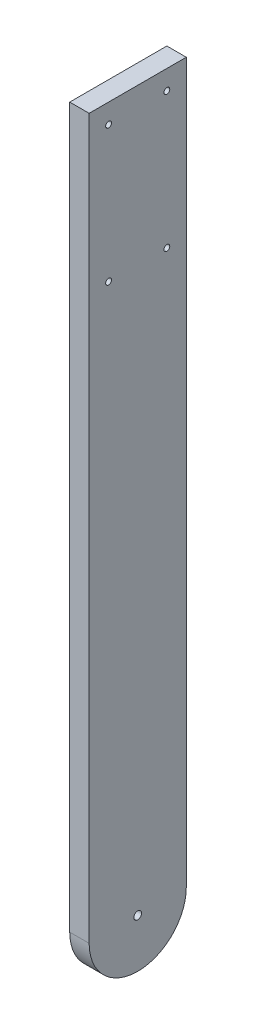
SolidWorks part; units mm, degrees
ref_plane "Front Plane" through (0, 0, 0) normal (0, 0, 1) x (1, 0, 0)
ref_plane "Top Plane" through (0, 0, 0) normal (0, 1, 0) x (1, 0, 0)
ref_plane "Right Plane" through (0, 0, 0) normal (1, 0, 0) x (0, 0, -1)
sketch "Sketch3" plane through (0, 0, 0) normal (1, 0, 0) x (0, 0, -1)
  line L1 (12.5, 100) -> (-12.5, 100)
  line L2 (12.5, 100) -> (12.5, -85)
  line L4 (-12.5, 100) -> (-12.5, -85)
  line L5 (12.5, 100) -> (-11.2945, -90.3558) construction
  line L6 (11.2945, -90.3558) -> (-12.5, 100) construction
  arc A0 (-12.5, -85) -> (12.5, -85) centre (0, -85) ccw
  point P0 (0, 0)
  point P5 (0, -85)
  dimension "D1" = 25
extrude "Boss-Extrude2" add sketch "Sketch3" along normal blind 5
sketch "Sketch4" plane through (0, 0, 0) normal (-1, 0, 0) x (0, 0, 1)
  line L0 (0, 51.9216) -> (0, 105.604) construction
  line L1 (-19.4199, 77.5) -> (19.8154, 77.5) construction
  line L2 (-12.5, 100) -> (12.5, 100) construction
  circle A0 centre (-7.5, 95) radius 0.75
  circle A1 centre (-7.5, 60) radius 0.75
  circle A2 centre (7.5, 60) radius 0.75
  circle A3 centre (7.5, 95) radius 0.75
  dimension "D1" = 7.5
  dimension "D2" = 1.5
  dimension "D3" = 5
  dimension "D4" = 39.2353
  dimension "D5" = 17.5
extrude "Cut-Extrude1" cut sketch "Sketch4" against normal blind 5
sketch "Sketch5" plane through (0, 0, 0) normal (-1, 0, 0) x (0, 0, 1)
  circle A0 centre (0, -85) radius 1
  arc A3 (-12.5, -85) -> (12.5, -85) centre (0, -85) ccw construction
  dimension "D2" = 2
  dimension "D3" = 11.5
extrude "Cut-Extrude2" cut sketch "Sketch5" against normal blind 5
